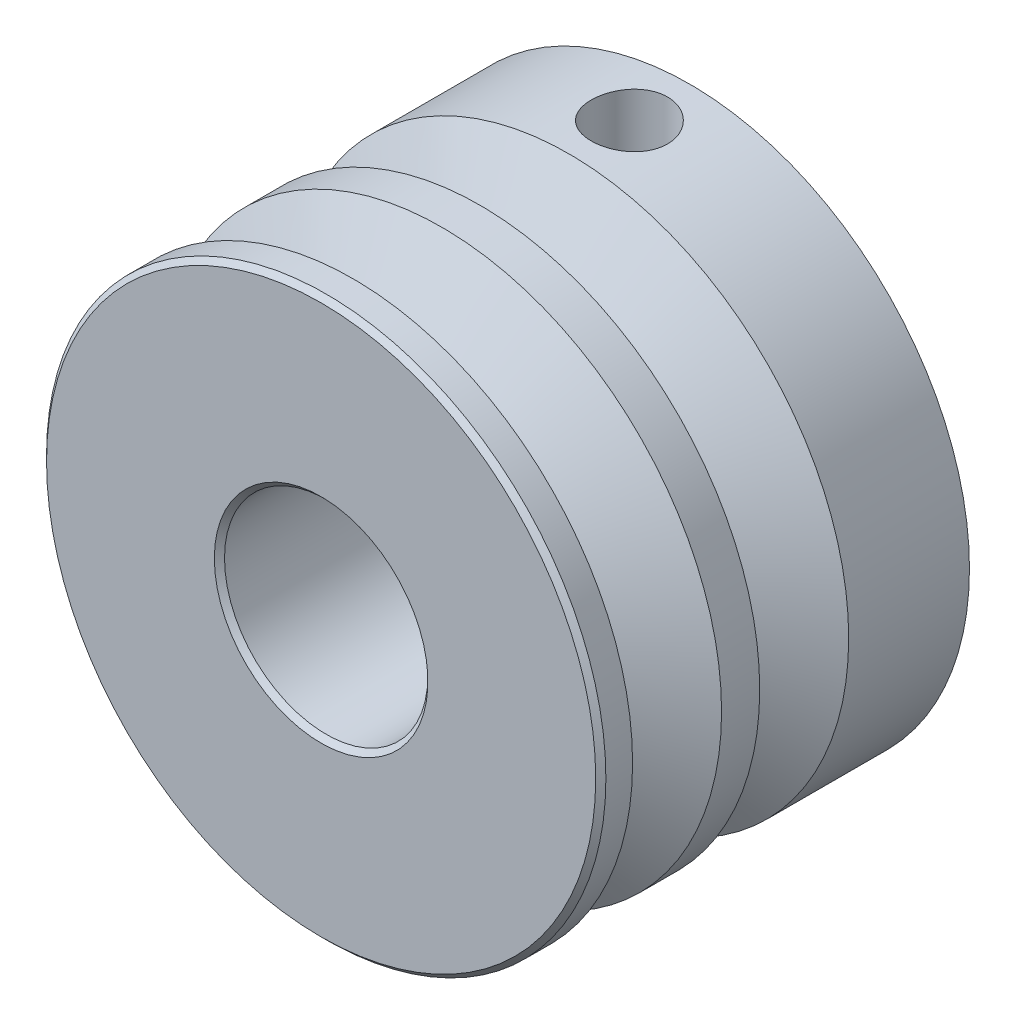
SolidWorks part; units mm, degrees
ref_plane "前视基准面" through (0, 0, 0) normal (0, 0, 1) x (1, 0, 0)
ref_plane "上视基准面" through (0, 0, 0) normal (0, 1, 0) x (1, 0, 0)
ref_plane "右视基准面" through (0, 0, 0) normal (1, 0, 0) x (0, 0, -1)
sketch "草图1" plane through (0, 0, 0) normal (1, 0, 0) x (0, 0, -1)
  line L0 (0, 0) -> (46.9269, 0) construction
  line L1 (0, 4) -> (15, 4)
  line L2 (0, 11) -> (1.25, 11)
  line L3 (1.25, 11) -> (2.9134, 8.1189)
  line L4 (3.0866, 8.1189) -> (4.75, 11)
  line L5 (4.75, 11) -> (6.25, 11)
  line L6 (6.25, 11) -> (7.9134, 8.1189)
  line L7 (8.0866, 8.1189) -> (9.75, 11)
  line L8 (9.75, 11) -> (14.5, 11)
  line L9 (15, 5) -> (15, 4)
  line L10 (0, 11) -> (0, 4)
  line L11 (14.5, 11) -> (14.5, 5)
  line L12 (14.5, 5) -> (15, 5)
  arc A0 (3.0866, 8.1189) -> (2.9134, 8.1189) centre (3, 8.1689) cw
  arc A1 (8.0866, 8.1189) -> (7.9134, 8.1189) centre (8, 8.1689) cw
  point P17 (3, 7.9689)
  point P20 (8, 7.9689)
  dimension "D13" = 0.1
  dimension "D1" = 4
  dimension "D2" = 7
  dimension "D3" = 3
  dimension "D4" = 1.25
  dimension "D5" = 3.5
  dimension "D6" = 5
  dimension "D7" = 60
  dimension "D8" = 3.5
  dimension "D9" = 15
  dimension "D10" = 0.5
  dimension "D11" = 5
revolve "旋转1" add sketch "草图1" angle 360 about L0
hole_wizard "M3 螺纹孔1" positions "草图3" profile "草图2" tap size "M3" standard "GB"
sketch "草图3" plane through (0, 0, 0) normal (0, 1, 0) x (1, 0, 0)
  line L0 (11, 14.5) -> (-11, 14.5) construction
  point P0 (0, 12.125)
  dimension "D1" = 2.375
sketch "草图2" plane through (0, 0, -12.125) normal (1, 0, 0) x (0, 0, -1)
  line L0 (0, 0) -> (0, 15.0263)
  line L1 (0, 15.0263) -> (1.5, 15.0263)
  line L2 (1.5, 15.0263) -> (1.5, 0)
  line L5 (1.5, 0) -> (0, 0)
  line L11 (0, -6.35) -> (0, 107.95) construction
  dimension "螺纹线主直径" = 3
  dimension "通孔螺纹孔钻头深度" = 15.0263
pattern_circular "阵列(圆周)1" count 2 every 120 about axis through (0, 0, 0) along (0, 0, 1) of "M3 螺纹孔1"
chamfer "倒角1" distance 0.2 angle 45 4 edges at (11, 0, 0) (4, 0, 0) (4, 0, -15) (5, 0, -15)
